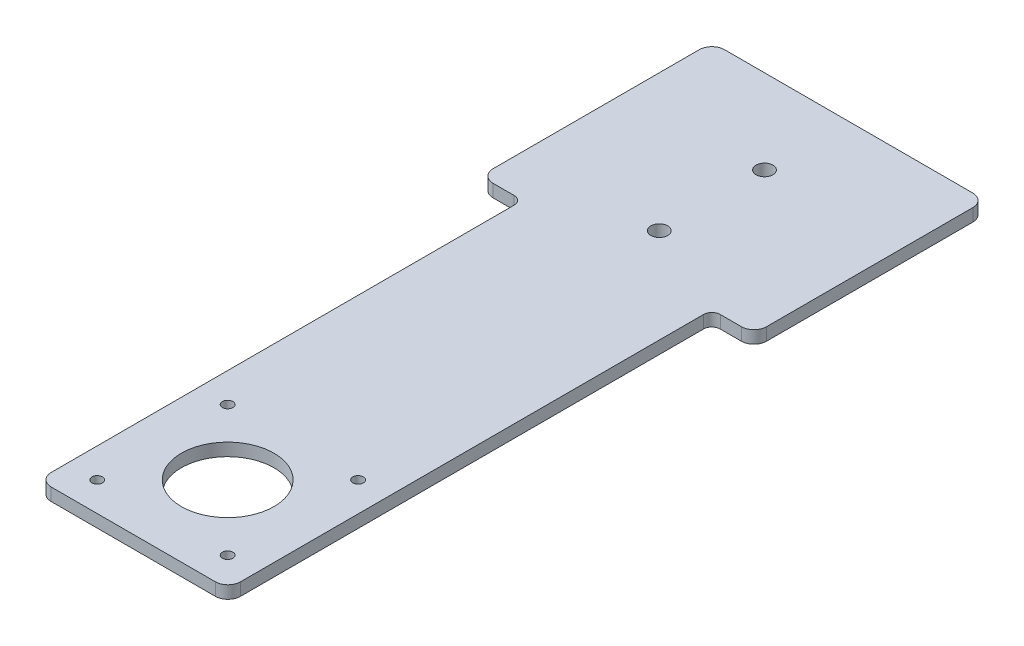
SolidWorks part; units mm, degrees
ref_plane "Front Plane" through (0, 0, 0) normal (0, 0, 1) x (1, 0, 0)
ref_plane "Top Plane" through (0, 0, 0) normal (0, 1, 0) x (1, 0, 0)
ref_plane "Right Plane" through (0, 0, 0) normal (1, 0, 0) x (0, 0, -1)
sketch "Sketch1" plane through (0, 0, 0) normal (0, 1, 0) x (1, 0, 0)
  line L1 (0, 28.9333) -> (0, -58.3864) construction
  line L2 (0, 111.6136) -> (-32.5, 111.6136)
  line L3 (0, 111.6136) -> (32.5, 111.6136)
  line L4 (0, -58.3864) -> (-22.5, -58.3864)
  line L5 (-22.5, -58.3864) -> (0, -58.3864)
  line L6 (0, -58.3864) -> (22.5, -58.3864)
  line L7 (0, 104.294) -> (0, 28.9333) construction
  line L8 (-32.5, 111.6136) -> (-32.5, 56.6136)
  line L9 (32.5, 111.6136) -> (32.5, 56.6136)
  line L10 (-22.5, -58.3864) -> (-22.5, 56.6136)
  line L11 (22.5, -58.3864) -> (22.5, 56.6136)
  line L12 (22.5, 56.6136) -> (32.5, 56.6136)
  line L13 (-32.5, 56.6136) -> (-22.5, 56.6136)
  line L14 (-15.5, -20.454) -> (15.5, -51.454) construction
  line L15 (-15.5, -51.454) -> (15.5, -20.454) construction
  circle A0 centre (0, 91.6136) radius 2
  circle A1 centre (0, 66.6136) radius 2
  circle A2 centre (-15.5, -20.454) radius 1.25
  circle A3 centre (-15.5, -51.454) radius 1.25
  circle A4 centre (15.5, -51.454) radius 1.25
  circle A5 centre (15.5, -20.454) radius 1.25
  circle A6 centre (0, -35.954) radius 11
  dimension "D10" = 2.5
  dimension "D11" = 2.5
  dimension "D12" = 4
  dimension "D13" = 4
  dimension "D16" = 31
  dimension "D17" = 22
  dimension "D1" = 32.5
  dimension "D2" = 32.5
  dimension "D3" = 22.5
  dimension "D4" = 22.5
  dimension "D5" = 170
  dimension "D6" = 55
  dimension "D7" = 55
  dimension "D8" = 15.5
  dimension "D9" = 15.5
  dimension "D14" = 20
  dimension "D15" = 45
sketch "Sketch2" plane through (0, 0, 0) normal (0, 1, 0) x (1, 0, 0)
extrude "Boss-Extrude1" add sketch "Sketch1" along normal blind 3 contours L8 L13 L10 L4 L6 L11 L12 L9 L3 L2
fillet "Fillet1" radius 3 1 edges at (32.5, 1.5, -111.6136)
fillet "Fillet2" radius 3 1 edges at (-32.5, 1.5, -111.6136)
fillet "Fillet3" radius 3 1 edges at (-32.5, 1.5, -56.6136)
fillet "Fillet4" radius 3 1 edges at (32.5, 1.5, -56.6136)
fillet "Fillet5" radius 3 1 edges at (22.5, 1.5, 58.3864)
fillet "Fillet7" radius 3 1 edges at (-22.5, 1.5, 58.3864)
fillet "Fillet8" radius 2 1 edges at (-22.5, 1.5, -56.6136)
fillet "Fillet9" radius 2 1 edges at (22.5, 1.5, -56.6136)
